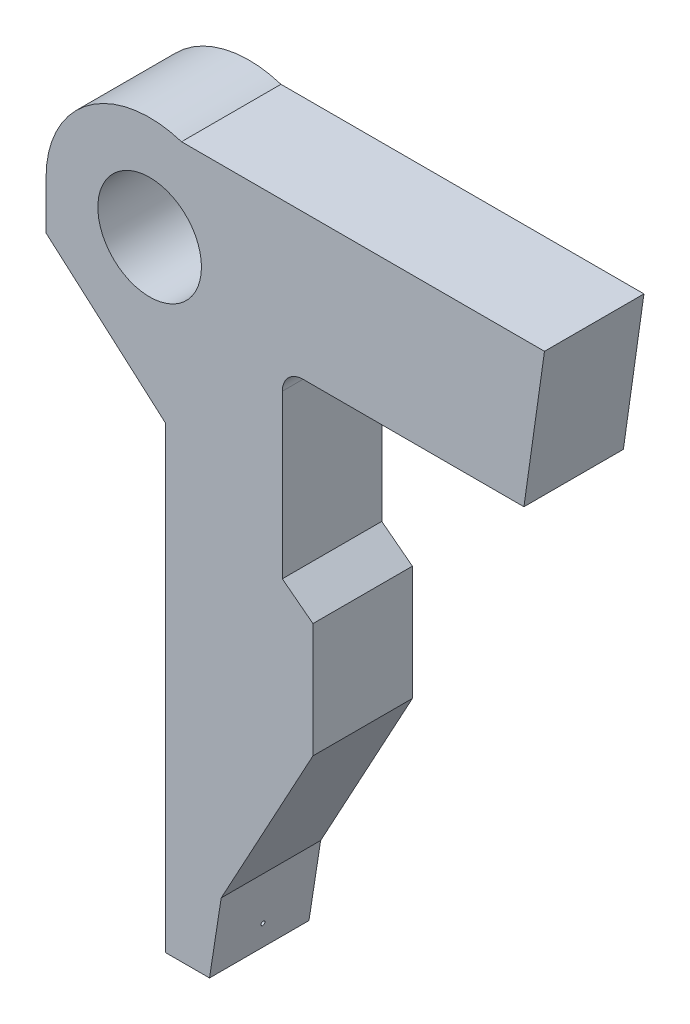
SolidWorks part; units mm, degrees
ref_plane "정면" through (0, 0, 0) normal (0, 0, 1) x (1, 0, 0)
ref_plane "윗면" through (0, 0, 0) normal (0, 1, 0) x (1, 0, 0)
ref_plane "우측면" through (0, 0, 0) normal (1, 0, 0) x (0, 0, -1)
sketch "스케치1" plane through (0, 0, 0) normal (0, 0, 1) x (1, 0, 0)
  line L0 (-5, 0) -> (-5, -2.3265)
  line L1 (0.7542, -29.5199) -> (2.8891, -29.5199)
  line L2 (6.4021, -11.0793) -> (6.4021, -3.2376)
  line L3 (7.4021, -2.2376) -> (18.0636, -2.2376)
  line L4 (18.0636, -2.2376) -> (19.056, 4.758)
  line L5 (2.8891, -29.5199) -> (3.4526, -25.8908)
  line L6 (-5, -2.3265) -> (0.7542, -7.3778)
  line L7 (0.7542, -7.3778) -> (0.7542, -29.5199)
  line L8 (19.056, 4.758) -> (1.5367, 4.758)
  line L9 (3.4526, -25.8908) -> (7.8804, -17.7409)
  line L10 (7.8804, -17.7409) -> (7.8804, -12.2111)
  line L11 (7.8804, -12.2111) -> (6.4021, -11.0793)
  circle A0 centre (0, 0) radius 2.5
  circle A1 centre (0, 0) radius 5
  arc A3 (6.4021, -3.2376) -> (7.4021, -2.2376) centre (7.4021, -3.2376) cw
  dimension "D1" = 5
  dimension "D2" = 10
  dimension "D3" = 1
extrude "보스-돌출1" add sketch "스케치1" along normal blind 4.8
sketch "스케치3" plane through (0.7542, 0, 0) normal (-1, 0, 0) x (0, 0, 1)
  line L0 (4.8, -29.5199) -> (0, -29.5199) construction
  circle A0 centre (2.4, -27.0199) radius 1.825
  point P2 (2.4, -29.5199)
  dimension "D2" = 3.65
  dimension "D1" = 2.5
extrude "컷-돌출1" cut sketch "스케치3" against normal blind 2
sketch "스케치4" plane through (2.7542, 0, 0) normal (-1, 0, 0) x (0, 0, 1)
  line L0 (2.4, -25.1949) -> (2.4, -28.8449) construction
  circle A0 centre (2.4, -27.0199) radius 1.825 construction
  circle A1 centre (2.4, -27.0199) radius 1.825 construction
  circle A2 centre (2.4, -28.3449) radius 0.1
  dimension "D1" = 0.5
extrude "컷-돌출2" cut sketch "스케치4" against normal up to next contours A2
